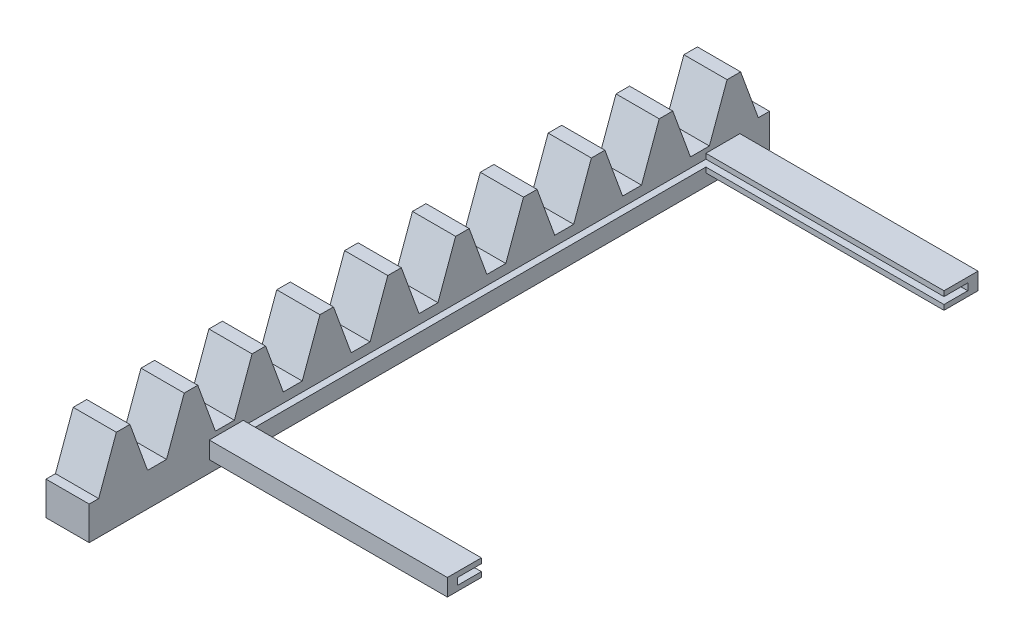
SolidWorks part; units mm, degrees
ref_plane "Front Plane" through (0, 0, 0) normal (0, 0, 1) x (1, 0, 0)
ref_plane "Top Plane" through (0, 0, 0) normal (0, 1, 0) x (1, 0, 0)
ref_plane "Right Plane" through (0, 0, 0) normal (1, 0, 0) x (0, 0, -1)
ref_plane "Plane1" through (22.5422, 0, 0) normal (-1, 0, 0) x (0, -1, 0)
sketch "Sketch1" plane through (22.5422, 0, 0) normal (-1, 0, 0) x (0, -1, 0)
  line L0 (-5.9102, -78.2114) -> (8.3773, -83.4116)
  line L1 (8.3773, -83.4116) -> (8.3773, -86.7046)
  line L2 (8.3773, -86.7046) -> (18.2198, -86.7046)
  line L3 (18.2198, -86.7046) -> (18.2198, 113.2955)
  line L4 (18.2198, 113.2955) -> (8.3773, 113.2955)
  line L5 (8.3773, 113.2955) -> (8.3773, 110.5114)
  line L6 (8.3773, 110.5114) -> (-5.9102, 105.3112)
  line L7 (-5.9102, 105.3112) -> (-5.9102, 101.3307)
  line L8 (-5.9102, 101.3307) -> (8.3773, 96.1304)
  line L9 (8.3773, 96.1304) -> (8.3773, 90.5623)
  line L10 (8.3773, 90.5623) -> (-5.9102, 85.3621)
  line L11 (-5.9102, 85.3621) -> (-5.9102, 81.3815)
  line L12 (-5.9102, 81.3815) -> (8.3773, 76.1813)
  line L13 (8.3773, 76.1813) -> (8.3773, 70.6132)
  line L14 (8.3773, 70.6132) -> (-5.9102, 65.413)
  line L15 (-5.9102, 65.413) -> (-5.9102, 61.4324)
  line L16 (-5.9102, 61.4324) -> (8.3773, 56.2322)
  line L17 (8.3773, 56.2322) -> (8.3773, 50.6641)
  line L18 (8.3773, 50.6641) -> (-5.9102, 45.4639)
  line L19 (-5.9102, 45.4639) -> (-5.9102, 41.4833)
  line L20 (-5.9102, 41.4833) -> (8.3773, 36.2831)
  line L21 (8.3773, 36.2831) -> (8.3773, 30.715)
  line L22 (8.3773, 30.715) -> (-5.9102, 25.5147)
  line L23 (-5.9102, 25.5147) -> (-5.9102, 21.5342)
  line L24 (-5.9102, 21.5342) -> (8.3773, 16.334)
  line L25 (8.3773, 16.334) -> (8.3773, 10.7658)
  line L26 (8.3773, 10.7658) -> (-5.9102, 5.5656)
  line L27 (-5.9102, 5.5656) -> (-5.9102, 1.5851)
  line L28 (-5.9102, 1.5851) -> (8.3773, -3.6151)
  line L29 (8.3773, -3.6151) -> (8.3773, -9.1833)
  line L30 (8.3773, -9.1833) -> (-5.9102, -14.3835)
  line L31 (-5.9102, -14.3835) -> (-5.9102, -18.364)
  line L32 (-5.9102, -18.364) -> (8.3773, -23.5642)
  line L33 (8.3773, -23.5642) -> (8.3773, -29.1324)
  line L34 (8.3773, -29.1324) -> (-5.9102, -34.3326)
  line L35 (-5.9102, -34.3326) -> (-5.9102, -38.3131)
  line L36 (-5.9102, -38.3131) -> (8.3773, -43.5134)
  line L37 (8.3773, -43.5134) -> (8.3773, -49.0815)
  line L38 (8.3773, -49.0815) -> (-5.9102, -54.2817)
  line L39 (-5.9102, -54.2817) -> (-5.9102, -58.2623)
  line L40 (-5.9102, -58.2623) -> (8.3773, -63.4625)
  line L41 (8.3773, -63.4625) -> (8.3773, -69.0306)
  line L42 (8.3773, -69.0306) -> (-5.9102, -74.2308)
  line L43 (-5.9102, -74.2308) -> (-5.9102, -78.2114)
extrude "Boss-Extrude1" add sketch "Sketch1" against normal blind 12.7
sketch "Sketch3" plane through (0, 0, 0) normal (0, 0, 1) x (1, 0, 0)
  line L0 (35.2422, -13.2198) -> (35.2422, -11.2198)
  line L1 (35.2422, -13.2198) -> (30.2422, -13.2198)
  line L2 (35.2422, -11.2198) -> (30.2422, -11.2198)
  line L3 (30.2422, -13.2198) -> (30.2422, -11.2198)
  line L4 (35.2422, -18.2198) -> (35.2422, -8.3773) construction
  line L5 (35.2422, -18.2198) -> (22.5422, -18.2198) construction
  dimension "D1" = 2
  dimension "D2" = 5
  dimension "D3" = 5
extrude "Cut-Extrude1" cut sketch "Sketch3" against normal mid plane 150
ref_plane "Plane3" through (35.2422, 0, 0) normal (1, 0, 0) x (0, 0, -1)
sketch "Sketch4" plane through (35.2422, 0, 0) normal (1, 0, 0) x (0, 0, -1)
  line L5 (75, -11.2198) -> (-75, -11.2198) construction
  line L6 (-78, -14.7198) -> (-68, -14.7198)
  line L12 (-78, -14.7198) -> (-78, -9.7198)
  line L13 (-78, -9.7198) -> (-68, -9.7198)
  line L24 (-68, -14.7198) -> (-68, -9.7198)
  line L25 (-78, -14.7198) -> (-68, -9.7198) construction
  line L26 (-78, -9.7198) -> (-68, -14.7198) construction
  line L27 (75, -13.2198) -> (75, -11.2198) construction
  line L28 (-75, -11.2198) -> (-75, -13.2198) construction
  line L29 (78, -14.7198) -> (68, -14.7198)
  line L30 (78, -14.7198) -> (78, -9.7198)
  line L31 (78, -9.7198) -> (68, -9.7198)
  line L32 (68, -14.7198) -> (68, -9.7198)
  line L33 (78, -14.7198) -> (68, -9.7198) construction
  line L34 (78, -9.7198) -> (68, -14.7198) construction
  line L35 (75, -13.2198) -> (-75, -13.2198) construction
  line L36 (75, -11.2198) -> (68, -11.2198)
  line L37 (75, -11.2198) -> (75, -13.2198)
  line L38 (75, -13.2198) -> (68, -13.2198)
  line L39 (68, -11.2198) -> (68, -13.2198)
  line L41 (-68, -11.2198) -> (-75, -11.2198)
  line L42 (-68, -11.2198) -> (-68, -13.2198)
  line L43 (-68, -13.2198) -> (-75, -13.2198)
  line L44 (-75, -11.2198) -> (-75, -13.2198)
  point P0 (-73, -12.2198)
  point P9 (73, -12.2198)
  dimension "D1" = 10
  dimension "D2" = 5
  dimension "D3" = 1
  dimension "D4" = 2
  dimension "D5" = 10
  dimension "D6" = 5
  dimension "D7" = 1
  dimension "D8" = 2
extrude "Boss-Extrude3" add sketch "Sketch4" along normal blind 70 contours L44 L41 L24 L13 L12 L6 L43 | L37 L38 L32 L29 L30 L31 L36
